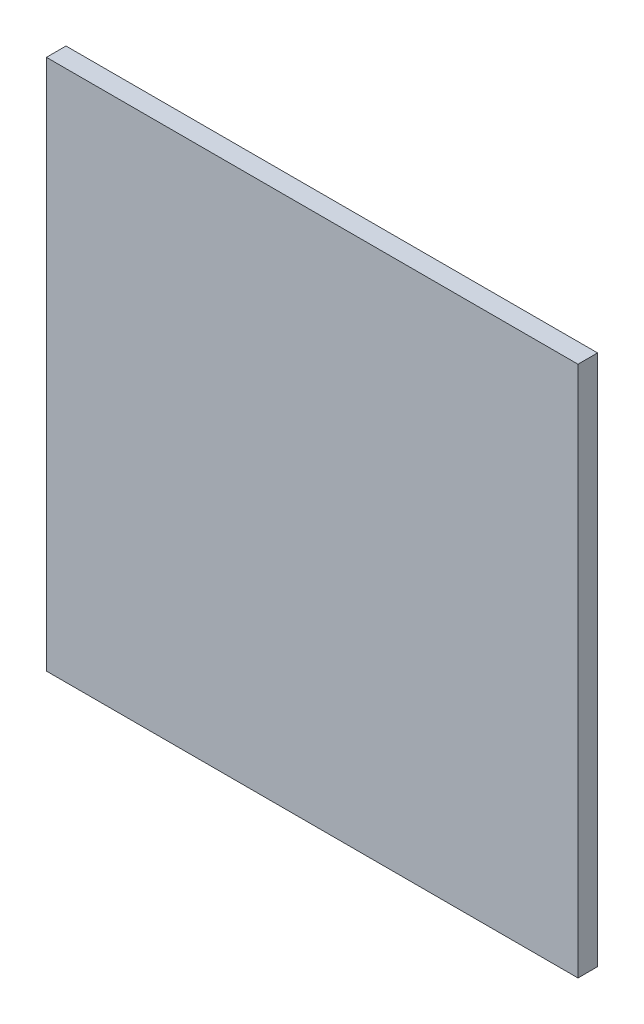
SolidWorks part; units mm, degrees
ref_plane "前视基准面" through (0, 0, 0) normal (0, 0, 1) x (1, 0, 0)
ref_plane "上视基准面" through (0, 0, 0) normal (0, 1, 0) x (1, 0, 0)
ref_plane "右视基准面" through (0, 0, 0) normal (1, 0, 0) x (0, 0, -1)
other "Configuration Table"
sketch "草图1" plane through (0, 0, 0.1778) normal (0, 0, -1) x (-1, 0, 0)
  line L1 (-5.2391, 30.6899) -> (-32.3783, 30.6899)
  line L2 (-5.2391, 30.6899) -> (-5.2391, 3.5507)
  line L3 (-5.2391, 3.5507) -> (-32.3783, 3.5507)
  line L4 (-32.3783, 30.6899) -> (-32.3783, 3.5507)
  dimension "D1" = 0.2
  dimension "D2" = 0.2
  dimension "D3" = 0.2
extrude "凸台-拉伸1" add sketch "草图1" along normal blind 1
